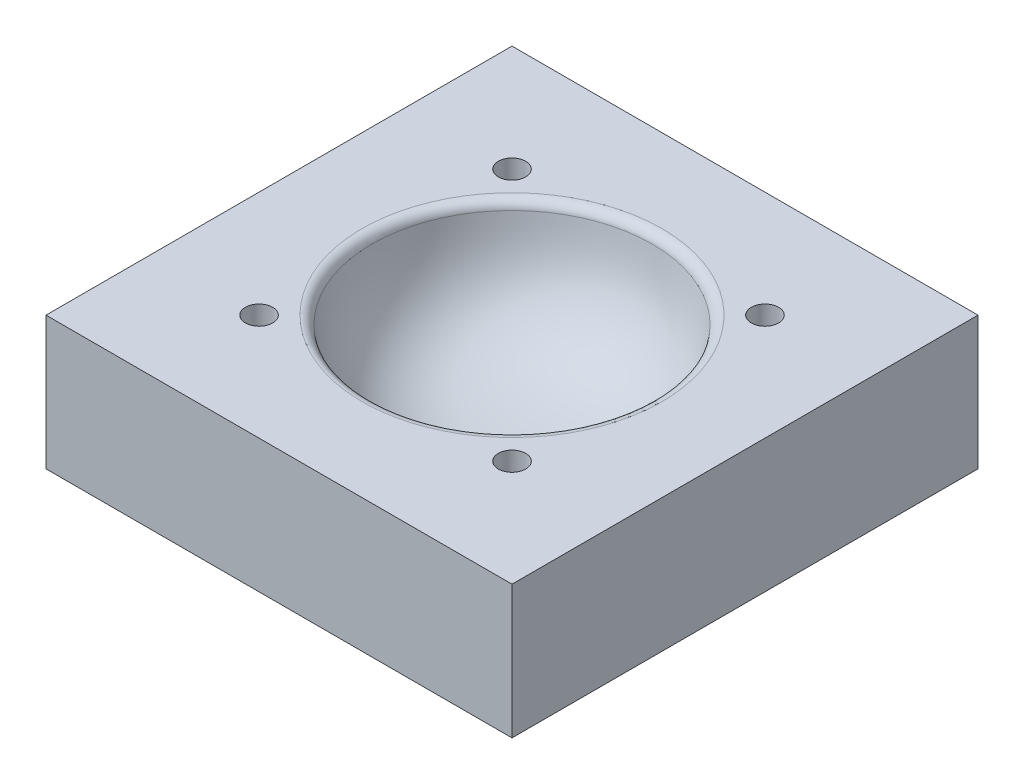
SolidWorks part; units mm, degrees
ref_plane "Front" through (0, 0, 0) normal (0, 0, 1) x (1, 0, 0)
ref_plane "Top" through (0, 0, 0) normal (0, 1, 0) x (1, 0, 0)
ref_plane "Right" through (0, 0, 0) normal (1, 0, 0) x (0, 0, -1)
sketch "Sketch2" plane through (0, 0, 0) normal (0, 1, 0) x (1, 0, 0)
  line L1 (-35, -35) -> (35, -35)
  line L2 (-35, -35) -> (-35, 35)
  line L3 (-35, 35) -> (35, 35)
  line L4 (35, -35) -> (35, 35)
  line L5 (-35, -35) -> (35, 35) construction
  line L6 (-35, 35) -> (35, -35) construction
  point P0 (0, 0)
  dimension "D1" = 70
extrude "Boss-Extrude1" add sketch "Sketch2" against normal blind 20
sketch "Sketch1" plane through (0, 0, 0) normal (0, 0, 1) x (1, 0, 0)
  line L0 (0, 0) -> (0, -14) construction
  line L1 (-15, 0) -> (15, 0) construction
  line L2 (-15, 0) -> (-15, -9) construction
  line L3 (-15, -9) -> (15, -9) construction
  line L4 (15, 0) -> (15, -9) construction
  line L5 (0, 0) -> (18, 0) construction
  line L6 (18, 0) -> (15.6756, -14.676) construction
  line L7 (-15, -20) -> (15, -20) construction
  line L8 (-15, -17) -> (15, -17) construction
  line L9 (-15, -14) -> (15, -14) construction
  line L10 (18, 0) -> (18, 4) construction
  line L11 (18, 4) -> (0, 4) construction
  line L12 (0, 4) -> (0, 0) construction
  line L13 (0, -17.2) -> (0, 0)
  line L14 (0, 0) -> (21.2417, 0)
  line L15 (-35, 0) -> (35, 0) construction
  line L16 (21.2417, 0) -> (21.1589, -0.5115)
  spline S0 degree 3 poles (0, -14) (16.3895, -14) (17.0195, -6.0548) (18, 0) knots 0 0 0 0 1 1 1 1 construction
  spline S1 degree 1 poles (0, -17.2) (21.1589, -0.5115) knots 0 0 1 1 construction
  spline S2 degree 3 poles (0, -17.2) (0.5307, -17.2) (1.6116, -17.1835) (3.6155, -17.0859) (5.9441, -16.8449) (8.4484, -16.3701) (11.4427, -15.4929) (14.5797, -13.9372) (17.3822, -11.4027) (19.199, -8.5009) (20.2357, -5.5832) (20.7065, -3.3134) (20.9819, -1.6359) (21.0969, -0.8942) (21.1589, -0.5115) knots 0 0 0 0 0.03125 0.0625 0.125 0.1875 0.25 0.375 0.5 0.625 0.75 0.875 0.9375 1 1 1 1
  dimension "D1" = 30
  dimension "D2" = 9
  dimension "D3" = 18
  dimension "D4" = 20
  dimension "D5" = 3
  dimension "D6" = 3
  dimension "D7" = 81
  dimension "D8" = 18
  dimension "D9" = 3.2
revolve "Cut-Revolve1" cut sketch "Sketch1" angle 360 about L13
fillet "Fillet1" radius 1.5 1 edges at (0, 0, -21.2417)
sketch "Sketch3" plane through (0, 0, 0) normal (0, 1, 0) x (1, 0, 0)
  line L0 (-32.7416, 0) -> (25.0655, 0) construction
  line L1 (-19, -19) -> (19, -19) construction
  line L2 (-19, -19) -> (-19, 19) construction
  line L3 (-19, 19) -> (19, 19) construction
  line L4 (19, -19) -> (19, 19) construction
  line L5 (-19, -19) -> (19, 19) construction
  line L6 (-19, 19) -> (19, -19) construction
  circle A0 centre (-19, 19) radius 2.05
  circle A1 centre (19, -19) radius 2.05
  circle A2 centre (-19, -19) radius 2.05
  circle A3 centre (19, 19) radius 2.05
  point P0 (0, 0)
  dimension "D2" = 4.1
  dimension "D1" = 38
extrude "Cut-Extrude1" cut sketch "Sketch3" against normal through all
